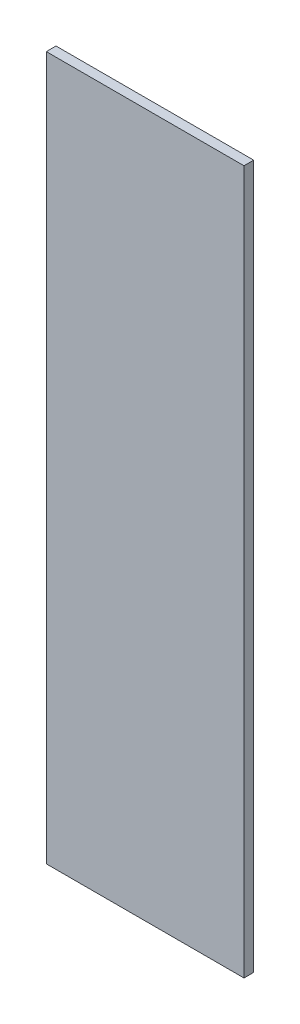
SolidWorks part; units mm, degrees
material "Thornel Mat VMA"
ref_plane "前视基准面" through (0, 0, 0) normal (0, 0, 1) x (1, 0, 0)
ref_plane "上视基准面" through (0, 0, 0) normal (0, 1, 0) x (1, 0, 0)
ref_plane "右视基准面" through (0, 0, 0) normal (1, 0, 0) x (0, 0, -1)
sketch "草图1" plane through (0, 0, 0) normal (0, 0, 1) x (1, 0, 0)
  line L1 (40.75, -145) -> (-40.75, -145)
  line L2 (40.75, -145) -> (40.75, 145)
  line L3 (40.75, 145) -> (-40.75, 145)
  line L4 (-40.75, -145) -> (-40.75, 145)
  line L5 (0, 145) -> (0, -145) construction
  line L6 (40.75, 0) -> (-40.75, 0) construction
  point P0 (0, 0)
  dimension "D1" = 81.5
  dimension "D2" = 290
extrude "凸台-拉伸1" add sketch "草图1" along normal blind 4
